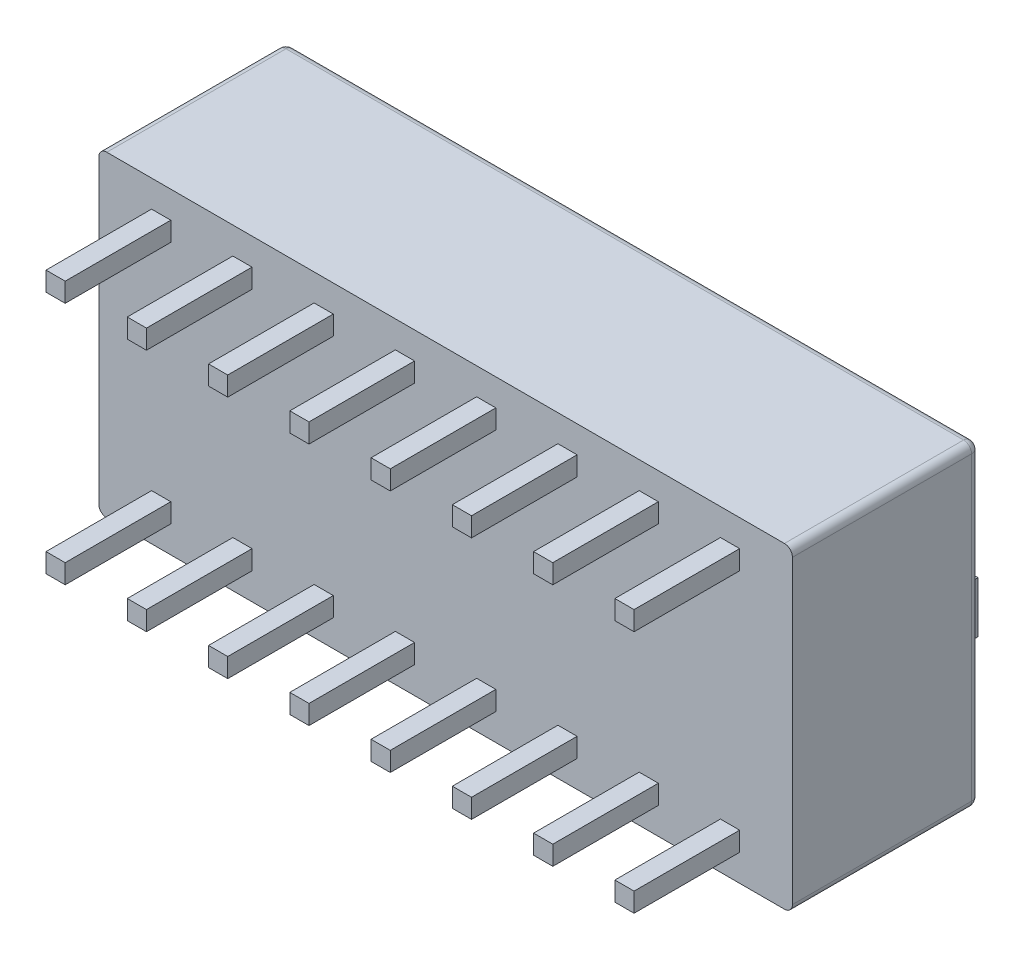
SolidWorks part; units mm, degrees
ref_plane "Ön Düzlem" through (0, 0, 0) normal (0, 0, 1) x (1, 0, 0)
ref_plane "Üst Düzlem" through (0, 0, 0) normal (0, 1, 0) x (1, 0, 0)
ref_plane "Sağ Düzlem" through (0, 0, 0) normal (1, 0, 0) x (0, 0, -1)
sketch "Çizim1" plane through (0, 0, 0) normal (0, 0, 1) x (1, 0, 0)
  line L1 (-10.84, 4.95) -> (10.84, 4.95)
  line L2 (-10.84, 4.95) -> (-10.84, -4.95)
  line L3 (-10.84, -4.95) -> (10.84, -4.95)
  line L4 (10.84, 4.95) -> (10.84, -4.95)
  line L5 (-10.84, 4.95) -> (10.84, -4.95) construction
  line L6 (-10.84, -4.95) -> (10.84, 4.95) construction
  point P0 (0, 0)
extrude "Yükseklik-Ekstrüzyon1" add sketch "Çizim1" along normal blind 5.85 contours L2 L1 L4 L3
sketch "Çizim2" plane through (0, 0, 0) normal (0, 0, -1) x (-1, 0, 0)
  line L9 (-9.59, 1.6) -> (-8.19, 1.6)
  line L10 (-9.59, 1.6) -> (-9.59, -1.6)
  line L11 (-9.59, -1.6) -> (-8.19, -1.6)
  line L12 (-8.19, 1.6) -> (-8.19, -1.6)
  line L13 (-9.59, 1.6) -> (-8.19, -1.6) construction
  line L14 (-9.59, -1.6) -> (-8.19, 1.6) construction
  line L15 (-7.05, 1.6) -> (-5.65, 1.6)
  line L16 (-7.05, 1.6) -> (-7.05, -1.6)
  line L17 (-7.05, -1.6) -> (-5.65, -1.6)
  line L18 (-5.65, 1.6) -> (-5.65, -1.6)
  line L19 (-7.05, 1.6) -> (-5.65, -1.6) construction
  line L20 (-7.05, -1.6) -> (-5.65, 1.6) construction
  line L21 (-4.51, 1.6) -> (-3.11, 1.6)
  line L22 (-4.51, 1.6) -> (-4.51, -1.6)
  line L23 (-4.51, -1.6) -> (-3.11, -1.6)
  line L24 (-3.11, 1.6) -> (-3.11, -1.6)
  line L25 (-4.51, 1.6) -> (-3.11, -1.6) construction
  line L26 (-4.51, -1.6) -> (-3.11, 1.6) construction
  line L27 (-1.97, 1.6) -> (-0.57, 1.6)
  line L28 (-1.97, 1.6) -> (-1.97, -1.6)
  line L29 (-1.97, -1.6) -> (-0.57, -1.6)
  line L30 (-0.57, 1.6) -> (-0.57, -1.6)
  line L31 (-1.97, 1.6) -> (-0.57, -1.6) construction
  line L32 (-1.97, -1.6) -> (-0.57, 1.6) construction
  line L33 (0.57, 1.6) -> (1.97, 1.6)
  line L34 (0.57, 1.6) -> (0.57, -1.6)
  line L35 (0.57, -1.6) -> (1.97, -1.6)
  line L36 (1.97, 1.6) -> (1.97, -1.6)
  line L37 (0.57, 1.6) -> (1.97, -1.6) construction
  line L38 (0.57, -1.6) -> (1.97, 1.6) construction
  line L39 (3.11, 1.6) -> (4.51, 1.6)
  line L40 (3.11, 1.6) -> (3.11, -1.6)
  line L41 (3.11, -1.6) -> (4.51, -1.6)
  line L42 (4.51, 1.6) -> (4.51, -1.6)
  line L43 (3.11, 1.6) -> (4.51, -1.6) construction
  line L44 (3.11, -1.6) -> (4.51, 1.6) construction
  line L45 (5.65, 1.6) -> (7.05, 1.6)
  line L46 (5.65, 1.6) -> (5.65, -1.6)
  line L47 (5.65, -1.6) -> (7.05, -1.6)
  line L48 (7.05, 1.6) -> (7.05, -1.6)
  line L49 (5.65, 1.6) -> (7.05, -1.6) construction
  line L50 (5.65, -1.6) -> (7.05, 1.6) construction
  line L51 (8.19, 1.6) -> (9.59, 1.6)
  line L52 (8.19, 1.6) -> (8.19, -1.6)
  line L53 (8.19, -1.6) -> (9.59, -1.6)
  line L54 (9.59, 1.6) -> (9.59, -1.6)
  line L55 (8.19, 1.6) -> (9.59, -1.6) construction
  line L56 (8.19, -1.6) -> (9.59, 1.6) construction
extrude "Kes-Ekstrüzyon1" cut sketch "Çizim2" against normal blind 1
sketch "Çizim3" plane through (0, 0, 1) normal (0, 0, -1) x (-1, 0, 0)
  line L0 (-8.19, -1.6) -> (-8.19, 1.6) construction
  line L1 (-9.59, -1.6) -> (-8.19, -1.6)
  line L2 (-9.59, -1.6) -> (-9.59, 0)
  line L3 (-9.59, 0) -> (-8.19, 0)
  line L4 (-8.19, -1.6) -> (-8.19, 0)
  line L5 (-7.05, 1.6) -> (-7.05, -1.6) construction
  line L6 (-7.05, 0) -> (-5.65, 0)
  line L7 (-7.05, 0) -> (-7.05, -1.6)
  line L8 (-7.05, -1.6) -> (-5.65, -1.6)
  line L9 (-5.65, 0) -> (-5.65, -1.6)
  line L10 (-4.51, 1.6) -> (-4.51, -1.6) construction
  line L11 (-4.51, 0) -> (-3.11, 0)
  line L12 (-4.51, 0) -> (-4.51, -1.6)
  line L13 (-4.51, -1.6) -> (-3.11, -1.6)
  line L14 (-3.11, 0) -> (-3.11, -1.6)
  line L15 (-0.57, -1.6) -> (-0.57, 1.6) construction
  line L16 (-1.97, -1.6) -> (-0.57, -1.6)
  line L17 (-1.97, -1.6) -> (-1.97, 0)
  line L18 (-1.97, 0) -> (-0.57, 0)
  line L19 (-0.57, -1.6) -> (-0.57, 0)
  line L20 (0.57, 1.6) -> (0.57, -1.6) construction
  line L21 (0.57, 0) -> (1.97, 0)
  line L22 (0.57, 0) -> (0.57, -1.6)
  line L23 (0.57, -1.6) -> (1.97, -1.6)
  line L24 (1.97, 0) -> (1.97, -1.6)
  line L25 (1.97, -1.6) -> (1.97, 1.6) construction
  line L26 (1.97, -1.6) -> (1.97, 1.6) construction
  line L27 (3.11, 1.6) -> (3.11, -1.6) construction
  line L28 (3.11, 0) -> (4.51, 0)
  line L29 (3.11, 0) -> (3.11, -1.6)
  line L30 (3.11, -1.6) -> (4.51, -1.6)
  line L31 (4.51, 0) -> (4.51, -1.6)
  line L32 (7.05, -1.6) -> (7.05, 1.6) construction
  line L33 (5.65, -1.6) -> (7.05, -1.6)
  line L34 (5.65, -1.6) -> (5.65, 0)
  line L35 (5.65, 0) -> (7.05, 0)
  line L36 (7.05, -1.6) -> (7.05, 0)
  line L37 (8.19, 1.6) -> (8.19, -1.6) construction
  line L38 (8.19, 0) -> (9.59, 0)
  line L39 (8.19, 0) -> (8.19, -1.6)
  line L40 (8.19, -1.6) -> (9.59, -1.6)
  line L41 (9.59, 0) -> (9.59, -1.6)
extrude "Yükseklik-Ekstrüzyon2" add sketch "Çizim3" along normal blind 2.2 separate body
sketch "Çizim4" plane through (0, 0, 1) normal (0, 0, -1) x (-1, 0, 0)
  line L0 (-5.65, -1.6) -> (-5.65, 1.6) construction
  line L1 (-9.59, 1.6) -> (-8.19, 1.6)
  line L2 (-9.59, 1.6) -> (-9.59, 0)
  line L3 (-9.59, 0) -> (-8.19, 0)
  line L4 (-8.19, 1.6) -> (-8.19, 0)
  line L5 (-7.05, 1.6) -> (-5.65, 1.6)
  line L6 (-7.05, 1.6) -> (-7.05, 0)
  line L7 (-7.05, 0) -> (-5.65, 0)
  line L8 (-5.65, 1.6) -> (-5.65, 0)
  line L9 (-3.11, -1.6) -> (-3.11, 1.6) construction
  line L10 (-4.51, 1.6) -> (-3.11, 1.6)
  line L11 (-4.51, 1.6) -> (-4.51, 0)
  line L12 (-4.51, 0) -> (-3.11, 0)
  line L13 (-3.11, 1.6) -> (-3.11, 0)
  line L14 (-0.57, -1.6) -> (-0.57, 1.6) construction
  line L15 (-1.97, 1.6) -> (-0.57, 1.6)
  line L16 (-1.97, 1.6) -> (-1.97, 0)
  line L17 (-1.97, 0) -> (-0.57, 0)
  line L18 (-0.57, 1.6) -> (-0.57, 0)
  line L19 (1.97, -1.6) -> (1.97, 1.6) construction
  line L20 (0.57, 1.6) -> (1.97, 1.6)
  line L21 (0.57, 1.6) -> (0.57, 0)
  line L22 (0.57, 0) -> (1.97, 0)
  line L23 (1.97, 1.6) -> (1.97, 0)
  line L24 (3.11, 1.6) -> (3.11, -1.6) construction
  line L25 (3.11, 0) -> (4.51, 0)
  line L26 (3.11, 0) -> (3.11, 1.6)
  line L27 (3.11, 1.6) -> (4.51, 1.6)
  line L28 (4.51, 0) -> (4.51, 1.6)
  line L29 (9.59, -1.6) -> (9.59, 1.6) construction
  line L30 (5.65, 1.6) -> (7.05, 1.6)
  line L31 (5.65, 1.6) -> (5.65, 0)
  line L32 (5.65, 0) -> (7.05, 0)
  line L33 (7.05, 1.6) -> (7.05, 0)
  line L34 (8.19, 1.6) -> (9.59, 1.6)
  line L35 (8.19, 1.6) -> (8.19, 0)
  line L36 (8.19, 0) -> (9.59, 0)
  line L37 (9.59, 1.6) -> (9.59, 0)
extrude "Yükseklik-Ekstrüzyon3" add sketch "Çizim4" along normal blind 0.9 separate body
fillet "Radyus1" radius 0.25 8 edges at (10.84, -4.95, 2.925) (10.84, 0, 0) (10.84, 4.95, 2.925) (0, -4.95, 0) (0, 4.95, 0) (-10.84, -4.95, 2.925) (-10.84, 0, 0) (-10.84, 4.95, 2.925)
sketch "Çizim5" plane through (0, 0, 5.85) normal (0, 0, 1) x (1, 0, 0)
  line L17 (-9.19, 4.11) -> (-8.59, 4.11)
  line L18 (-9.19, 4.11) -> (-9.19, 3.51)
  line L19 (-9.19, 3.51) -> (-8.59, 3.51)
  line L20 (-8.59, 4.11) -> (-8.59, 3.51)
  line L21 (-9.19, 4.11) -> (-8.59, 3.51) construction
  line L22 (-9.19, 3.51) -> (-8.59, 4.11) construction
  line L23 (-6.65, 4.11) -> (-6.05, 4.11)
  line L24 (-6.65, 4.11) -> (-6.65, 3.51)
  line L25 (-6.65, 3.51) -> (-6.05, 3.51)
  line L26 (-6.05, 4.11) -> (-6.05, 3.51)
  line L27 (-6.65, 4.11) -> (-6.05, 3.51) construction
  line L28 (-6.65, 3.51) -> (-6.05, 4.11) construction
  line L29 (-4.11, 4.11) -> (-3.51, 4.11)
  line L30 (-4.11, 4.11) -> (-4.11, 3.51)
  line L31 (-4.11, 3.51) -> (-3.51, 3.51)
  line L32 (-3.51, 4.11) -> (-3.51, 3.51)
  line L33 (-4.11, 4.11) -> (-3.51, 3.51) construction
  line L34 (-4.11, 3.51) -> (-3.51, 4.11) construction
  line L35 (-1.57, 4.11) -> (-0.97, 4.11)
  line L36 (-1.57, 4.11) -> (-1.57, 3.51)
  line L37 (-1.57, 3.51) -> (-0.97, 3.51)
  line L38 (-0.97, 4.11) -> (-0.97, 3.51)
  line L39 (-1.57, 4.11) -> (-0.97, 3.51) construction
  line L40 (-1.57, 3.51) -> (-0.97, 4.11) construction
  line L41 (0.97, 4.11) -> (1.57, 4.11)
  line L42 (0.97, 4.11) -> (0.97, 3.51)
  line L43 (0.97, 3.51) -> (1.57, 3.51)
  line L44 (1.57, 4.11) -> (1.57, 3.51)
  line L45 (0.97, 4.11) -> (1.57, 3.51) construction
  line L46 (0.97, 3.51) -> (1.57, 4.11) construction
  line L47 (3.51, 4.11) -> (4.11, 4.11)
  line L48 (3.51, 4.11) -> (3.51, 3.51)
  line L49 (3.51, 3.51) -> (4.11, 3.51)
  line L50 (4.11, 4.11) -> (4.11, 3.51)
  line L51 (3.51, 4.11) -> (4.11, 3.51) construction
  line L52 (3.51, 3.51) -> (4.11, 4.11) construction
  line L53 (6.05, 4.11) -> (6.65, 4.11)
  line L54 (6.05, 4.11) -> (6.05, 3.51)
  line L55 (6.05, 3.51) -> (6.65, 3.51)
  line L56 (6.65, 4.11) -> (6.65, 3.51)
  line L57 (6.05, 4.11) -> (6.65, 3.51) construction
  line L58 (6.05, 3.51) -> (6.65, 4.11) construction
  line L59 (9.19, 4.11) -> (8.59, 4.11)
  line L60 (9.19, 4.11) -> (9.19, 3.51)
  line L61 (9.19, 3.51) -> (8.59, 3.51)
  line L62 (8.59, 4.11) -> (8.59, 3.51)
  line L63 (9.19, 4.11) -> (8.59, 3.51) construction
  line L64 (9.19, 3.51) -> (8.59, 4.11) construction
  line L65 (8.59, -4.11) -> (9.19, -4.11)
  line L66 (8.59, -4.11) -> (8.59, -3.51)
  line L67 (8.59, -3.51) -> (9.19, -3.51)
  line L68 (9.19, -4.11) -> (9.19, -3.51)
  line L69 (8.59, -4.11) -> (9.19, -3.51) construction
  line L70 (8.59, -3.51) -> (9.19, -4.11) construction
  line L71 (6.05, -4.11) -> (6.65, -4.11)
  line L72 (6.05, -4.11) -> (6.05, -3.51)
  line L73 (6.05, -3.51) -> (6.65, -3.51)
  line L74 (6.65, -4.11) -> (6.65, -3.51)
  line L75 (6.05, -4.11) -> (6.65, -3.51) construction
  line L76 (6.05, -3.51) -> (6.65, -4.11) construction
  line L77 (3.51, -4.11) -> (4.11, -4.11)
  line L78 (3.51, -4.11) -> (3.51, -3.51)
  line L79 (3.51, -3.51) -> (4.11, -3.51)
  line L80 (4.11, -4.11) -> (4.11, -3.51)
  line L81 (3.51, -4.11) -> (4.11, -3.51) construction
  line L82 (3.51, -3.51) -> (4.11, -4.11) construction
  line L83 (0.97, -4.11) -> (1.57, -4.11)
  line L84 (0.97, -4.11) -> (0.97, -3.51)
  line L85 (0.97, -3.51) -> (1.57, -3.51)
  line L86 (1.57, -4.11) -> (1.57, -3.51)
  line L87 (0.97, -4.11) -> (1.57, -3.51) construction
  line L88 (0.97, -3.51) -> (1.57, -4.11) construction
  line L89 (-1.57, -4.11) -> (-0.97, -4.11)
  line L90 (-1.57, -4.11) -> (-1.57, -3.51)
  line L91 (-1.57, -3.51) -> (-0.97, -3.51)
  line L92 (-0.97, -4.11) -> (-0.97, -3.51)
  line L93 (-1.57, -4.11) -> (-0.97, -3.51) construction
  line L94 (-1.57, -3.51) -> (-0.97, -4.11) construction
  line L95 (-4.11, -4.11) -> (-3.51, -4.11)
  line L96 (-4.11, -4.11) -> (-4.11, -3.51)
  line L97 (-4.11, -3.51) -> (-3.51, -3.51)
  line L98 (-3.51, -4.11) -> (-3.51, -3.51)
  line L99 (-4.11, -4.11) -> (-3.51, -3.51) construction
  line L100 (-4.11, -3.51) -> (-3.51, -4.11) construction
  line L101 (-6.65, -4.11) -> (-6.05, -4.11)
  line L102 (-6.65, -4.11) -> (-6.65, -3.51)
  line L103 (-6.65, -3.51) -> (-6.05, -3.51)
  line L104 (-6.05, -4.11) -> (-6.05, -3.51)
  line L105 (-6.65, -4.11) -> (-6.05, -3.51) construction
  line L106 (-6.65, -3.51) -> (-6.05, -4.11) construction
  line L107 (-9.19, -4.11) -> (-8.59, -4.11)
  line L108 (-9.19, -4.11) -> (-9.19, -3.51)
  line L109 (-9.19, -3.51) -> (-8.59, -3.51)
  line L110 (-8.59, -4.11) -> (-8.59, -3.51)
  line L111 (-9.19, -4.11) -> (-8.59, -3.51) construction
  line L112 (-9.19, -3.51) -> (-8.59, -4.11) construction
extrude "Yükseklik-Ekstrüzyon4" add sketch "Çizim5" along normal blind 3.3
